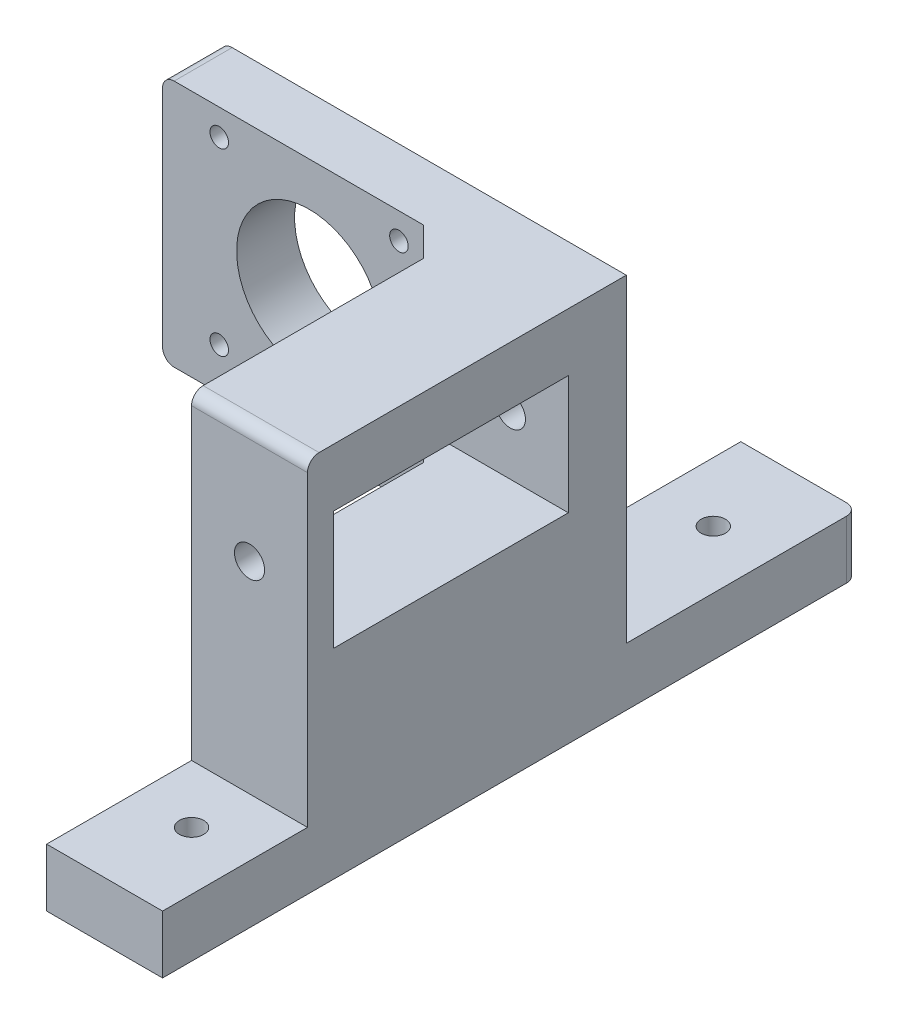
SolidWorks part; units mm, degrees
ref_plane "Front Plane" through (0, 0, 0) normal (0, 0, 1) x (1, 0, 0)
ref_plane "Top Plane" through (0, 0, 0) normal (0, 1, 0) x (1, 0, 0)
ref_plane "Right Plane" through (0, 0, 0) normal (1, 0, 0) x (0, 0, -1)
sketch "Sketch4" plane through (0, 0, 0) normal (0, 1, 0) x (1, 0, 0)
  line L1 (0, 0) -> (20, 0)
  line L2 (0, 0) -> (0, 120)
  line L3 (0, 120) -> (20, 120)
  line L4 (20, 0) -> (20, 120)
  dimension "D1" = 120
  dimension "D2" = 20
extrude "Boss-Extrude4" add sketch "Sketch4" along normal blind 10
sketch "Sketch5" plane through (0, 10, 0) normal (0, 1, 0) x (1, 0, 0)
  line L0 (10, 0) -> (10, 15) construction
  line L1 (0, 0) -> (20, 0) construction
  line L2 (10, 120) -> (10, 105) construction
  line L3 (20, 120) -> (0, 120) construction
  circle A0 centre (10, 105) radius 2.1
  circle A1 centre (10, 15) radius 2.1
  dimension "D3" = 4.2
  dimension "D4" = 4.2
  dimension "D1" = 15
  dimension "D2" = 15
extrude "Cut-Extrude1" cut sketch "Sketch5" against normal blind 10
sketch "Sketch8" plane through (0, 10, 0) normal (0, 1, 0) x (1, 0, 0)
  line L0 (20, 0) -> (20, 120) construction
  line L1 (20, 25) -> (0, 25)
  line L2 (20, 25) -> (20, 80)
  line L3 (20, 80) -> (0, 80)
  line L4 (0, 25) -> (0, 80)
  line L5 (0, 0) -> (20, 0) construction
  dimension "D1" = 55
  dimension "D2" = 20
  dimension "D3" = 25
extrude "Boss-Extrude6" add sketch "Sketch8" along normal blind 55
sketch "Sketch9" plane through (0, 0, 0) normal (-1, 0, 0) x (0, 0, 1)
  line L0 (-80, 65) -> (-80, 10) construction
  line L5 (-70, 55) -> (-29.5, 55)
  line L6 (-70, 55) -> (-70, 34.5)
  line L7 (-70, 34.5) -> (-29.5, 34.5)
  line L8 (-29.5, 55) -> (-29.5, 34.5)
  line L9 (-80, 65) -> (-25, 65) construction
  dimension "D1" = 20.5
  dimension "D2" = 40.5
  dimension "D3" = 10
  dimension "D4" = 10
extrude "Cut-Extrude2" cut sketch "Sketch9" against normal blind 20
sketch "Sketch11" plane through (0, 0, -70) normal (0, 0, 1) x (1, 0, 0)
  line L0 (0, 44.75) -> (20, 44.75)
  line L1 (0, 55) -> (0, 34.5) construction
  line L2 (20, 55) -> (20, 34.5) construction
  circle A0 centre (10, 44.75) radius 2.6
  dimension "D1" = 5.2
extrude "Cut-Extrude3" cut sketch "Sketch11" against normal mid plane 100 contours A0
sketch "Sketch12" plane through (0, 0, 0) normal (-1, 0, 0) x (0, 0, 1)
  line L1 (-80, 65) -> (-70, 65)
  line L2 (-80, 65) -> (-80, 10)
  line L3 (-80, 10) -> (-70, 10)
  line L4 (-70, 65) -> (-70, 10)
  dimension "D1" = 55
  dimension "D2" = 10
extrude "Boss-Extrude7" add sketch "Sketch12" along normal blind 50
sketch "Sketch15" plane through (0, 0, -70) normal (0, 0, 1) x (1, 0, 0)
  line L0 (0, 65) -> (20, 65) construction
  line L1 (-40.2253, 60.5002) -> (-9.2253, 60.5002)
  line L2 (-40.2253, 60.5002) -> (-40.2253, 29.5002)
  line L3 (-40.2253, 29.5002) -> (-9.2253, 29.5002)
  line L4 (-9.2253, 60.5002) -> (-9.2253, 29.5002)
  line L5 (-40.2253, 60.5002) -> (-9.2253, 29.5002) construction
  line L6 (-40.2253, 29.5002) -> (-9.2253, 60.5002) construction
  line L7 (-50, 10) -> (-50, 65) construction
  line L8 (-50, 65) -> (0, 65) construction
  circle A0 centre (-24.7253, 45.0002) radius 12.5
  circle A1 centre (-9.2253, 60.5002) radius 1.6
  circle A2 centre (-9.2253, 29.5002) radius 1.6
  circle A3 centre (-40.2253, 29.5002) radius 1.6
  circle A4 centre (-40.2253, 60.5002) radius 1.6
  point P19 (-24.7253, 45.0002)
  dimension "D1" = 25
  dimension "D6" = 3.2
  dimension "D2" = 31
  dimension "D3" = 19.9998
  dimension "D4" = 9.7747
  dimension "D5" = 4.4998
extrude "Cut-Extrude4" cut sketch "Sketch15" against normal up to surface (10 mm away) contours A0 | L4 A1 L1 | L1 A1 L4 | L3 A2 L4 | L4 A2 L3 | L2 A3 L3 | L3 A3 L2 | L2 A4 L1 | L1 A4 L2 up to face at (12.6, 44.75, -80)
sketch "Sketch17" plane through (0, 0, -70) normal (0, 0, 1) x (1, 0, 0)
  line L1 (-50, 10) -> (0, 10)
  line L2 (-50, 10) -> (-50, 22.25)
  line L3 (-50, 22.25) -> (0, 22.25)
  line L4 (0, 10) -> (0, 22.25)
  line L5 (0, 10) -> (0, 34.5) construction
  dimension "D1" = 12.25
  dimension "D2" = 50
extrude "Cut-Extrude6" cut sketch "Sketch17" against normal up to surface (10 mm away) contours L2 L1 L4 L3 up to face at (-38.6253, 60.5002, -80)
chamfer "Chamfer1" distance 12.5 angle 45 1 edges at (0, 22.25, -75)
fillet "Fillet1" radius 2 5 edges at (20, 5, -120) (0, 4.875, -120) (10, 65, -25) (-50, 65, -75) (-50, 22.25, -75)
chamfer "Chamfer2" distance 5 angle 45 2 edges at (0, 22.125, -70) (0, 60, -70)
